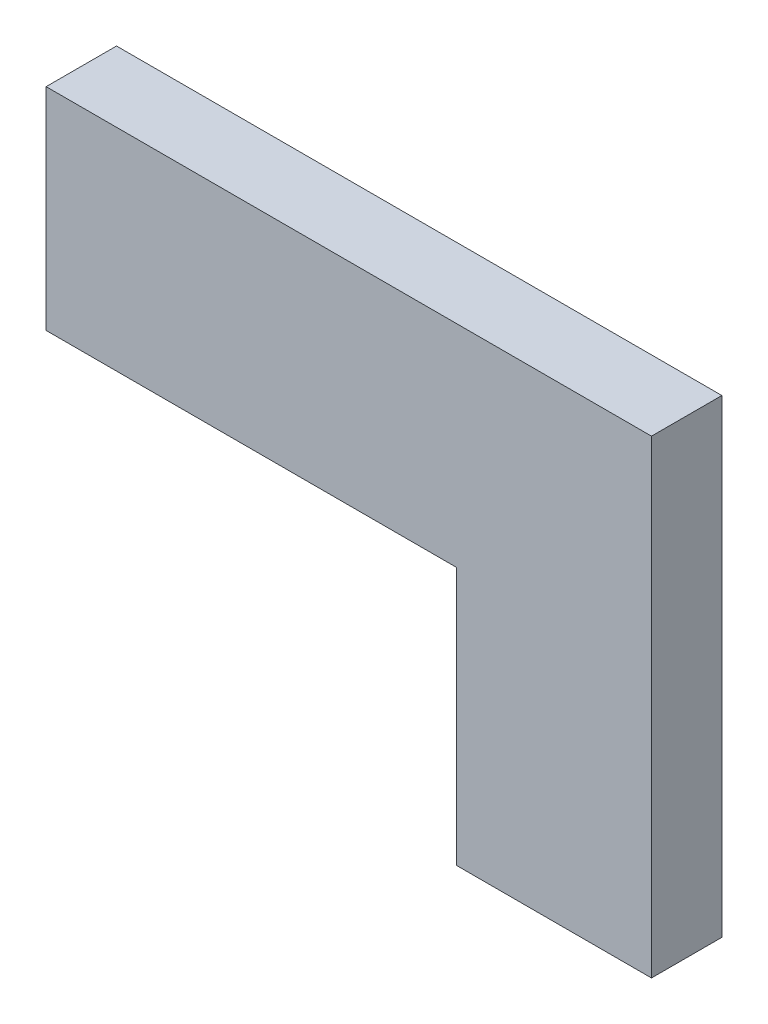
SolidWorks part; units mm, degrees
ref_plane "Front Plane" through (0, 0, 0) normal (0, 0, 1) x (1, 0, 0)
ref_plane "Top Plane" through (0, 0, 0) normal (0, 1, 0) x (1, 0, 0)
ref_plane "Right Plane" through (0, 0, 0) normal (1, 0, 0) x (0, 0, -1)
sketch "Sketch1" plane through (0, 0, 0) normal (0, 0, 1) x (1, 0, 0)
  line L1 (-2.5, 202.5) -> (255.5, 202.5)
  line L2 (-2.5, 202.5) -> (-2.5, 112.5)
  line L3 (-2.5, 112.5) -> (172.5, 112.5)
  line L6 (255.5, 2.5) -> (172.5, 2.5)
  line L7 (255.5, 2.5) -> (255.5, 202.5)
  line L9 (172.5, 2.5) -> (172.5, 112.5)
  dimension "D1" = 110
  dimension "D2" = 175
extrude "Boss-Extrude1" add sketch "Sketch1" along normal up to surface (30 mm away)
equation "\"TubingShort\" = 110mm"
equation "\"D1@Sketch1\"=\"TubingShort\""
equation "\"TubingLong\" = 175mm"
equation "\"D2@Sketch1\"=\"TubingLong\""
equation "\"Length\" = 283mm"
equation "\"Width\" = 225mm"
equation "\"WallThickness\" = 12.5mm"
equation "\"UpperWaterJacketThickness\" = 28mm"
equation "\"SpacerHeight\" = 80.2mm"
equation "\"PlateLength\" = 252mm"
equation "\"PlateWidth\" = 190mm"
equation "\"PlateHoleDiameter\" = 5.9mm"
equation "\"PlateHoleBottom\" = 2mm"
equation "\"PlateHoleSide\" = 1.55mm"
equation "\"PlateHoleSpacing\" = 3.1mm"
equation "\"PlateThickness\" = 1.55mm"
equation "\"ReservoirBottom\" = 12.5mm"
equation "\"ReservoirSupportWidth\" = 12mm"
equation "\"ReservoirSupportHeight\" = 15.1mm"
equation "\"ReservoirSupportPlacementHeight\" = 50mm"
equation "\"ReservoirHoleDiameter\" = 12.7mm"
equation "\"ReservoirHoleRight\" = 25mm"
equation "\"ReservoirHoleTop\"= \"ReservoirSupportPlacementHeight\""
equation "\"ReservoirHeight\" = 90mm"
equation "\"ReservoirPortBottom\" = 4mm"
equation "\"ReservoirPortTop\" = 10mm"
equation "\"ReservoirPortWidth\" = 101mm"
